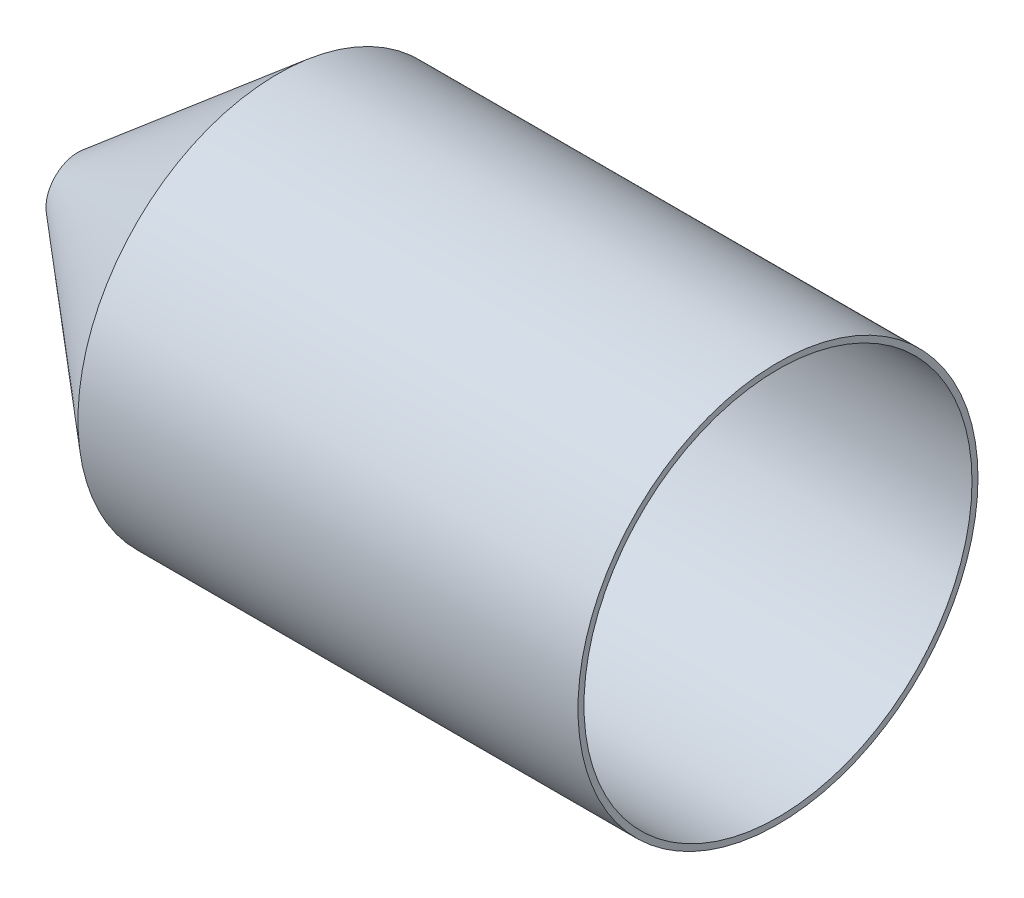
SolidWorks part; units mm, degrees
material "AISI 304"
ref_plane "Front Plane" through (0, 0, 0) normal (0, 0, 1) x (1, 0, 0)
ref_plane "Top Plane" through (0, 0, 0) normal (0, 1, 0) x (1, 0, 0)
ref_plane "Right Plane" through (0, 0, 0) normal (1, 0, 0) x (0, 0, -1)
sketch "Sketch1" plane through (0, 0, 0) normal (1, 0, 0) x (0, 0, -1)
  circle A0 centre (0, 0) radius 100
  circle A1 centre (0, 0) radius 97
  dimension "D1" = 200
  dimension "D2" = 3
extrude "Boss-Extrude1" add sketch "Sketch1" along normal blind 250
sketch "Sketch2" plane through (0, 0, 0) normal (1, 0, 0) x (0, 0, -1)
  circle A0 centre (0, 0) radius 100
  dimension "D1" = 200
ref_plane "Plane1" through (-100, 0, 0) normal (1, 0, 0) x (0, 0, -1)
sketch "Sketch3" plane through (-100, 0, 0) normal (1, 0, 0) x (0, 0, -1)
  circle A0 centre (0, 0) radius 16
  dimension "D1" = 32
surface "Surface-Loft1"
